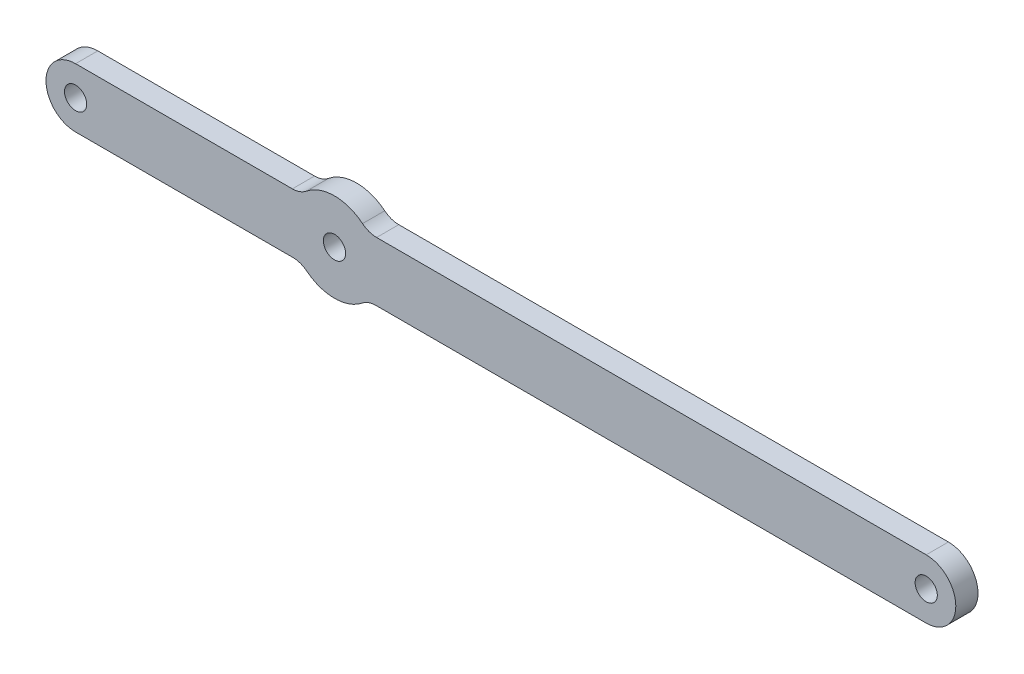
SolidWorks part; units mm, degrees
ref_plane "Plan de face" through (0, 0, 0) normal (0, 0, 1) x (1, 0, 0)
ref_plane "Plan de dessus" through (0, 0, 0) normal (0, 1, 0) x (1, 0, 0)
ref_plane "Plan de droite" through (0, 0, 0) normal (1, 0, 0) x (0, 0, -1)
sketch "Esquisse15" plane through (0, 0, 0) normal (0, 0, 1) x (1, 0, 0)
  line L0 (101.9102, 73.7175) -> (216.9102, 73.7175) construction
  line L1 (101.9102, 77.7175) -> (131.2168, 77.7175)
  line L2 (101.9102, 69.7175) -> (131.2902, 69.7175)
  line L3 (142.6035, 77.7175) -> (216.9102, 77.7175)
  line L4 (142.5301, 69.7175) -> (216.9102, 69.7175)
  circle A0 centre (101.9102, 73.7175) radius 1.5
  circle A1 centre (216.9102, 73.7175) radius 1.5
  circle A2 centre (136.9102, 73.7472) radius 1.5
  arc A3 (133.1635, 69.0607) -> (140.6568, 69.0607) centre (136.9102, 73.7472) ccw
  arc A4 (101.9102, 77.7175) -> (101.9102, 69.7175) centre (101.9102, 73.7175) ccw
  arc A5 (216.9102, 69.7175) -> (216.9102, 77.7175) centre (216.9102, 73.7175) ccw
  arc A6 (140.7057, 78.3941) -> (133.1146, 78.3941) centre (136.9102, 73.7472) ccw
  arc A7 (131.2902, 69.7175) -> (133.1635, 69.0607) centre (131.2902, 66.7175) cw
  arc A8 (140.6568, 69.0607) -> (142.5301, 69.7175) centre (142.5301, 66.7175) cw
  arc A9 (142.6035, 77.7175) -> (140.7057, 78.3941) centre (142.6035, 80.7175) cw
  arc A10 (133.1146, 78.3941) -> (131.2168, 77.7175) centre (131.2168, 80.7175) cw
  point P7 (159.4102, 73.7175)
  point P19 (141.3556, 69.7175)
  point P22 (141.4087, 77.7175)
  dimension "D1" = 3
  dimension "D2" = 3
  dimension "D3" = 4
  dimension "D4" = 12
  dimension "D5" = 3
  dimension "D6" = 35
  dimension "D7" = 115
  dimension "D8" = 3
extrude "Boss.-Extru.15" add sketch "Esquisse15" along normal blind 3 separate body
